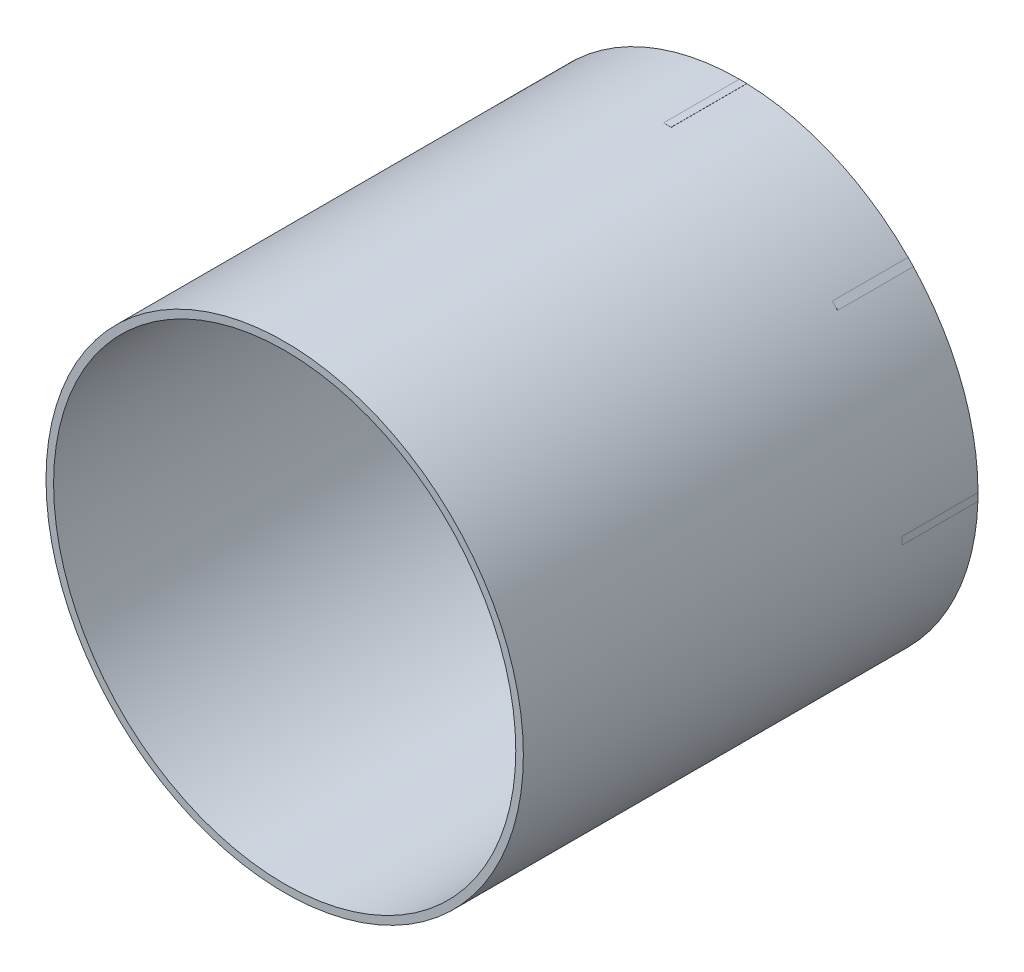
SolidWorks part; units mm, degrees
ref_plane "前视基准面" through (0, 0, 0) normal (0, 0, 1) x (1, 0, 0)
ref_plane "上视基准面" through (0, 0, 0) normal (0, 1, 0) x (1, 0, 0)
ref_plane "右视基准面" through (0, 0, 0) normal (1, 0, 0) x (0, 0, -1)
sketch "草图1" plane through (0, 0, 0) normal (0, 0, 1) x (1, 0, 0)
  circle A0 centre (0, 0) radius 30.5
extrude "拉伸-薄壁1" add sketch "草图1" along normal blind 60 thin
sketch "草图2" plane through (0, 0, 0) normal (0, 0, 1) x (1, 0, 0)
  line L0 (0, 0) -> (31.5, 0)
  line L1 (0, 0) -> (0, -1)
  line L2 (31.5, 0) -> (31.5, -1)
  line L3 (0, -1) -> (31.5, -1)
  circle A0 centre (0, 0) radius 31.5 construction
extrude "凸台-拉伸1" add sketch "草图2" along normal blind 10
pattern_circular "阵列(圆周)1" count 8 over 360 about axis through (0, 0, 0) along (0, 0, 1) of "凸台-拉伸1"
sketch "草图3" plane through (0, 0, 10) normal (0, 0, 1) x (1, 0, 0)
  circle A0 centre (0, 0) radius 12
extrude "凸台-拉伸2" add sketch "草图3" against normal blind 3
sketch "草图4" plane through (0, 0, 7) normal (0, 0, -1) x (-1, 0, 0)
  line L0 (0.0088, 0.0042) -> (-6.3361, -3.0099) construction
  line L1 (0, 0) -> (5.9269, -12.4764) construction
  circle A0 centre (-7.2261, -3.4327) radius 1.6
  circle A1 centre (4.0764, -8.581) radius 1.6
  circle A2 centre (0, 0) radius 5.1
  point P2 (0, 0)
  point P10 (-7.2261, -3.4327)
  dimension "D1" = 8
  dimension "D2" = 9.5
extrude "切除-拉伸1" cut sketch "草图4" against normal blind 5 contours A0 | A1 | A2
pattern_circular "阵列(圆周)3" count 2 over 360 about axis through (0, 0, 0) along (0, 0, 1) of "切除-拉伸1"
